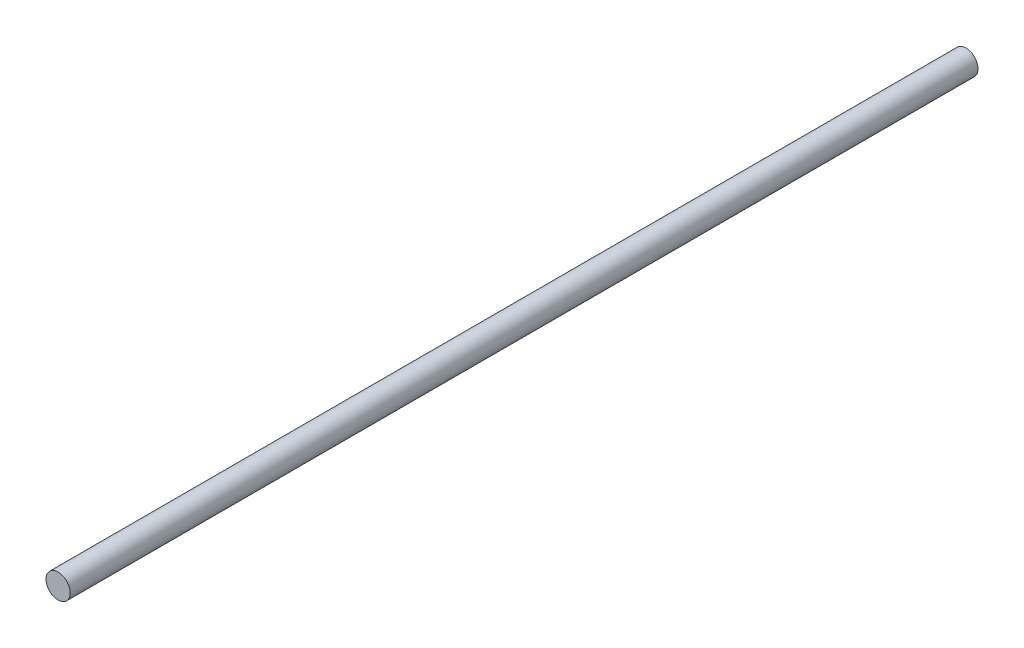
SolidWorks part; units mm, degrees
ref_plane "Front Plane" through (0, 0, 0) normal (0, 0, 1) x (1, 0, 0)
ref_plane "Top Plane" through (0, 0, 0) normal (0, 1, 0) x (1, 0, 0)
ref_plane "Right Plane" through (0, 0, 0) normal (1, 0, 0) x (0, 0, -1)
sketch "Sketch1" plane through (0, 0, 0) normal (0, 1, 0) x (1, 0, 0)
  line L0 (0, 50) -> (0, -50) construction
  dimension "D1" = 100
  dimension "D2" = 50
sketch "Sketch2" plane through (0, 0, 0) normal (0, 0, 1) x (1, 0, 0)
  circle A0 centre (0, 0) radius 1
  dimension "D1" = 2
extrude "Boss-Extrude1" add sketch "Sketch2" along normal mid plane 75
